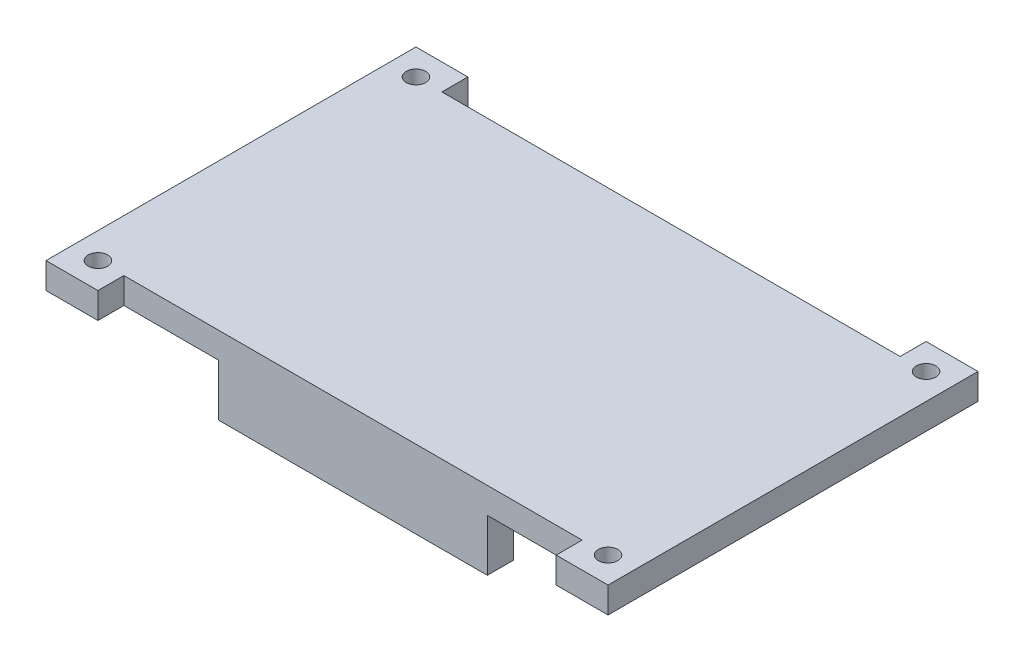
SolidWorks part; units mm, degrees
ref_plane "Front Plane" through (0, 0, 0) normal (0, 0, 1) x (1, 0, 0)
ref_plane "Top Plane" through (0, 0, 0) normal (0, 1, 0) x (1, 0, 0)
ref_plane "Right Plane" through (0, 0, 0) normal (1, 0, 0) x (0, 0, -1)
sketch "Sketch1" plane through (0, -22.3685, 0) normal (0, 1, 0) x (1, 0, 0)
  line L0 (27.9746, 63.7566) -> (27.9746, 61.7566) construction
  line L1 (27.9746, 61.7566) -> (31.9746, 61.7566) construction
  line L2 (31.9746, 61.7566) -> (31.9746, 41.2566) construction
  line L3 (31.9746, 41.2566) -> (22.9746, 41.2566) construction
  line L4 (22.9746, 41.2566) -> (22.9746, 39.2566) construction
  line L5 (22.9746, 39.2566) -> (29.9746, 39.2566) construction
  line L6 (29.9746, 39.2566) -> (29.9746, 37.2566) construction
  line L7 (29.9746, 37.2566) -> (33.9746, 37.2566) construction
  line L8 (33.9746, 37.2566) -> (33.9746, 65.7566) construction
  line L9 (33.9746, 65.7566) -> (29.9746, 65.7566) construction
  line L10 (29.9746, 65.7566) -> (29.9746, 63.7566) construction
  line L11 (29.9746, 63.7566) -> (27.9746, 63.7566) construction
  line L12 (1.6746, 61.7566) -> (1.6746, 63.7566) construction
  line L13 (1.6746, 63.7566) -> (-5.3254, 63.7566) construction
  line L14 (-5.3254, 63.7566) -> (-5.3254, 65.7566) construction
  line L15 (-5.3254, 65.7566) -> (-9.3254, 65.7566) construction
  line L16 (-9.3254, 65.7566) -> (-9.3254, 37.2566) construction
  line L17 (-9.3254, 37.2566) -> (-5.3254, 37.2566) construction
  line L18 (-5.3254, 37.2566) -> (-5.3254, 39.2566) construction
  line L19 (-5.3254, 39.2566) -> (1.6746, 39.2566) construction
  line L20 (1.6746, 39.2566) -> (1.6746, 41.2566) construction
  line L21 (1.6746, 41.2566) -> (-7.3254, 41.2566) construction
  line L22 (-7.3254, 41.2566) -> (-7.3254, 61.7566) construction
  line L23 (-7.3254, 61.7566) -> (1.6746, 61.7566) construction
  line L24 (27.9746, 63.7566) -> (27.9746, 61.7566)
  line L25 (27.9746, 61.7566) -> (31.9746, 61.7566)
  line L26 (31.9746, 61.7566) -> (31.9746, 41.2566)
  line L27 (31.9746, 41.2566) -> (22.9746, 41.2566)
  line L28 (22.9746, 41.2566) -> (22.9746, 39.2566)
  line L29 (22.9746, 39.2566) -> (29.9746, 39.2566)
  line L30 (29.9746, 39.2566) -> (29.9746, 37.2566)
  line L31 (29.9746, 37.2566) -> (33.9746, 37.2566)
  line L32 (33.9746, 37.2566) -> (33.9746, 65.7566)
  line L33 (33.9746, 65.7566) -> (29.9746, 65.7566)
  line L34 (29.9746, 65.7566) -> (29.9746, 63.7566)
  line L35 (29.9746, 63.7566) -> (27.9746, 63.7566)
  line L36 (1.6746, 61.7566) -> (1.6746, 63.7566)
  line L37 (1.6746, 63.7566) -> (-5.3254, 63.7566)
  line L38 (-5.3254, 63.7566) -> (-5.3254, 65.7566)
  line L39 (-5.3254, 65.7566) -> (-9.3254, 65.7566)
  line L40 (-9.3254, 65.7566) -> (-9.3254, 37.2566)
  line L41 (-9.3254, 37.2566) -> (-5.3254, 37.2566)
  line L42 (-5.3254, 37.2566) -> (-5.3254, 39.2566)
  line L43 (-5.3254, 39.2566) -> (1.6746, 39.2566)
  line L44 (1.6746, 39.2566) -> (1.6746, 41.2566)
  line L45 (1.6746, 41.2566) -> (-7.3254, 41.2566)
  line L46 (-7.3254, 41.2566) -> (-7.3254, 61.7566)
  line L47 (-7.3254, 61.7566) -> (1.6746, 61.7566)
  line L48 (1.6746, 63.7566) -> (27.9746, 63.7566)
  line L49 (1.6746, 39.2566) -> (22.9746, 39.2566)
  circle A0 centre (31.9746, 63.7566) radius 0.75 construction
  circle A1 centre (31.9746, 39.2566) radius 0.75 construction
  circle A2 centre (-7.3254, 39.2566) radius 0.75 construction
  circle A3 centre (-7.3254, 63.7566) radius 0.75 construction
  circle A4 centre (31.9746, 63.7566) radius 0.75
  circle A5 centre (31.9746, 39.2566) radius 0.75
  circle A6 centre (-7.3254, 39.2566) radius 0.75
  circle A7 centre (-7.3254, 63.7566) radius 0.75
  line M25 (1.6746, 61.7566) -> (1.6746, 63.7566)
  line M26 (1.6746, 63.7566) -> (-5.3254, 63.7566)
  line M27 (-5.3254, 63.7566) -> (-5.3254, 65.7566)
  line M28 (-5.3254, 65.7566) -> (-9.3254, 65.7566)
  line M29 (-9.3254, 65.7566) -> (-9.3254, 37.2566)
  line M30 (-9.3254, 37.2566) -> (-5.3254, 37.2566)
  line M31 (-5.3254, 37.2566) -> (-5.3254, 39.2566)
  line M32 (-5.3254, 39.2566) -> (1.6746, 39.2566)
  line M33 (1.6746, 39.2566) -> (1.6746, 41.2566)
  line M34 (1.6746, 41.2566) -> (-7.3254, 41.2566)
  line M35 (-7.3254, 41.2566) -> (-7.3254, 61.7566)
  line M36 (-7.3254, 61.7566) -> (1.6746, 61.7566)
  circle M37 centre (-7.3254, 63.7566) radius 0.75
  circle M38 centre (-7.3254, 39.2566) radius 0.75
extrude "Boss-Extrude1" add sketch "Sketch1" along normal blind 2 contours M36 M25 M26 M27 M28 M29 M30 M31 M32 M33 M34 M35 M37 M38 | L49 L28 L27 L26 L25 L24 L48 M33 M25 M36 M35 M34 | L34 L35 L24 L25 L26 L27 L28 L29 L30 L31 L32 L33 A5 A4
sketch "Sketch2" plane through (0, -22.3685, 0) normal (0, -1, 0) x (1, 0, 0)
  line L0 (-5.3254, -39.2566) -> (29.9746, -39.2566) construction
  line L1 (1.9746, -39.2566) -> (22.6746, -39.2566)
  line L2 (1.9746, -39.2566) -> (1.9746, -41.2566)
  line L3 (1.9746, -41.2566) -> (22.6746, -41.2566)
  line L4 (22.6746, -39.2566) -> (22.6746, -41.2566)
  line L5 (1.6746, -41.2566) -> (1.6746, -39.2566) construction
  line L6 (22.9746, -39.2566) -> (22.9746, -41.2566) construction
  line L7 (29.9746, -63.7566) -> (-5.3254, -63.7566) construction
  line L8 (27.6746, -63.7566) -> (1.9746, -63.7566)
  line L9 (27.6746, -63.7566) -> (27.6746, -61.7566)
  line L10 (27.6746, -61.7566) -> (1.9746, -61.7566)
  line L11 (1.9746, -63.7566) -> (1.9746, -61.7566)
  line L12 (27.9746, -61.7566) -> (27.9746, -63.7566) construction
  line L13 (1.6746, -63.7566) -> (1.6746, -61.7566) construction
  dimension "D1" = 0.3
  dimension "D2" = 2
  dimension "D3" = 0.3
  dimension "D4" = 2
  dimension "D5" = 0.3
  dimension "D6" = 0.3
extrude "Boss-Extrude2" add sketch "Sketch2" along normal blind 4
